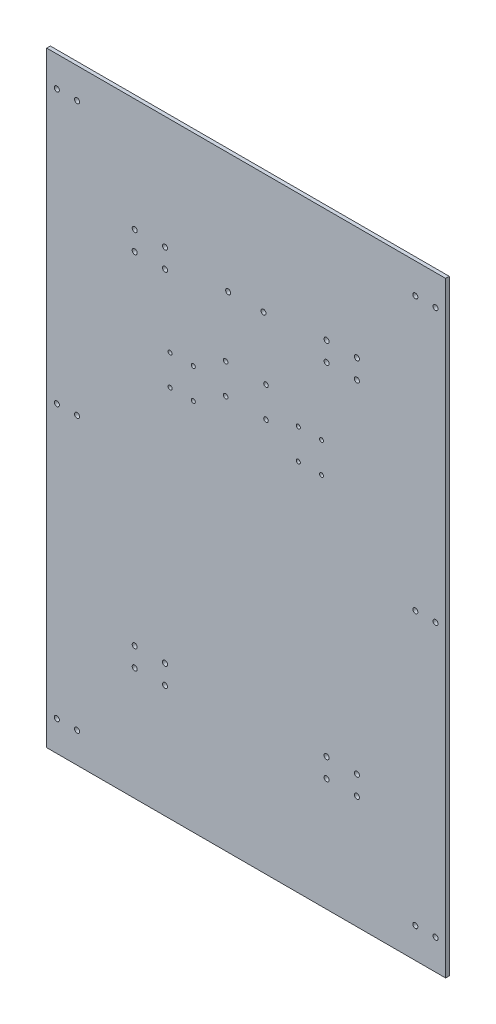
SolidWorks part; units mm, degrees
material "处理板，复杂型"
ref_plane "前视基准面" through (0, 0, 0) normal (0, 0, 1) x (1, 0, 0)
ref_plane "上视基准面" through (0, 0, 0) normal (0, 1, 0) x (1, 0, 0)
ref_plane "右视基准面" through (0, 0, 0) normal (1, 0, 0) x (0, 0, -1)
sketch "草图1" plane through (0, 0, 0) normal (0, 0, 1) x (1, 0, 0)
  line L0 (0, 25.8706) -> (0, -31.2111) construction
  line L1 (-225, 300) -> (170, 300)
  line L2 (-225, 300) -> (-225, -300)
  line L3 (-225, -300) -> (170, -300)
  line L4 (170, 300) -> (170, -300)
  line L5 (-23.9883, 0) -> (45.7004, 0) construction
  dimension "D1" = 395
  dimension "D2" = 600
  dimension "D3" = 225
  dimension "D4" = 300
extrude "凸台-拉伸1" add sketch "草图1" along normal blind 3.6
sketch "草图4" plane through (0, 0, 3.6) normal (0, 0, 1) x (1, 0, 0)
  line L0 (0, 355.7202) -> (0, -488.737) construction
  line L1 (-385.3696, 0) -> (469.6692, 0) construction
  line L2 (-195, 355.7202) -> (-195, -398.416) construction
  line L3 (140, -398.416) -> (140, 398.416) construction
  line L4 (-371.3197, 270) -> (369.3125, 270) construction
  line L5 (-343.2198, -270) -> (413.4695, -270) construction
  line L6 (170, -300) -> (170, 300) construction
  line L8 (-225, 300) -> (-225, -300) construction
  line L9 (-225, -300) -> (170, -300) construction
  line L10 (-205, -325.8576) -> (-205, 461.6631) construction
  line L11 (205, -325.8576) -> (205, 461.6631) construction
  circle A0 centre (-195, 270) radius 2.5
  circle A1 centre (-195, -270) radius 2.5
  circle A4 centre (-195, 0) radius 2.5
  circle A7 centre (-215, -270) radius 2.5
  circle A8 centre (-215, 0) radius 2.5
  circle A9 centre (-215, 270) radius 2.5
  dimension "D5" = 5
  dimension "D7" = 5
  dimension "D10" = 5
  dimension "D1" = 30
  dimension "D3" = 30
  dimension "D4" = 30
  dimension "D11" = 10
extrude "切除-拉伸3" cut sketch "草图4" against normal blind 3.6
sketch "草图5" plane through (0, 0, 3.6) normal (0, 0, 1) x (1, 0, 0)
  circle A0 centre (-102.8839, 69.956) radius 2
  circle A1 centre (-102.8839, 99.956) radius 2
  circle A2 centre (-79.8839, 69.956) radius 2
  circle A3 centre (-79.8839, 99.956) radius 2
extrude "切除-拉伸4" cut sketch "草图5" against normal blind 10
sketch "草图6" plane through (0, 0, 3.6) normal (0, 0, 1) x (1, 0, 0)
  circle A0 centre (24.1161, 69.956) radius 2
  circle A1 centre (24.1161, 99.956) radius 2
  circle A2 centre (47.1161, 69.956) radius 2
  circle A3 centre (47.1161, 99.956) radius 2
extrude "切除-拉伸5" cut sketch "草图6" against normal blind 10
sketch "草图7" plane through (0, 0, 3.6) normal (0, 0, 1) x (1, 0, 0)
  circle A0 centre (-45.3839, 180.956) radius 2.5
  circle A1 centre (-10.3839, 180.956) radius 2.5
extrude "切除-拉伸6" cut sketch "草图7" against normal blind 10
sketch "草图8" plane through (0, 0, 3.6) normal (0, 0, 1) x (1, 0, 0)
  circle A0 centre (-47.8839, 89.956) radius 2.25
  circle A1 centre (-47.8839, 119.956) radius 2.25
  circle A2 centre (-7.8839, 89.956) radius 2.25
  circle A3 centre (-7.8839, 119.956) radius 2.25
extrude "切除-拉伸7" cut sketch "草图8" against normal through all
sketch "草图9" plane through (0, 0, 3.6) normal (0, 0, 1) x (1, 0, 0)
  circle A0 centre (-137.8839, -188.044) radius 2.5
  circle A1 centre (-137.8839, -169.044) radius 2.5
  circle A2 centre (-107.8839, -188.044) radius 2.5
  circle A3 centre (-107.8839, -169.044) radius 2.5
  circle A4 centre (52.1161, -188.044) radius 2.5
  circle A5 centre (52.1161, -169.044) radius 2.5
  circle A6 centre (82.1161, -169.044) radius 2.5
  circle A7 centre (82.1161, -188.044) radius 2.5
  circle A8 centre (82.1161, 168.956) radius 2.5
  circle A9 centre (82.1161, 187.956) radius 2.5
  circle A10 centre (52.1161, 168.956) radius 2.5
  circle A11 centre (52.1161, 187.956) radius 2.5
  circle A12 centre (-107.8839, 168.956) radius 2.5
  circle A13 centre (-107.8839, 187.956) radius 2.5
  circle A14 centre (-137.8839, 168.956) radius 2.5
  circle A15 centre (-137.8839, 187.956) radius 2.5
extrude "切除-拉伸8" cut sketch "草图9" against normal through all
ref_plane "基准面1" through (-27.5, 0, 0) normal (-1, 0, 0) x (0, 0, 1)
mirror "镜向1" about plane through (-27.5, 0, 0) normal (-1, 0, 0) of "切除-拉伸3"
